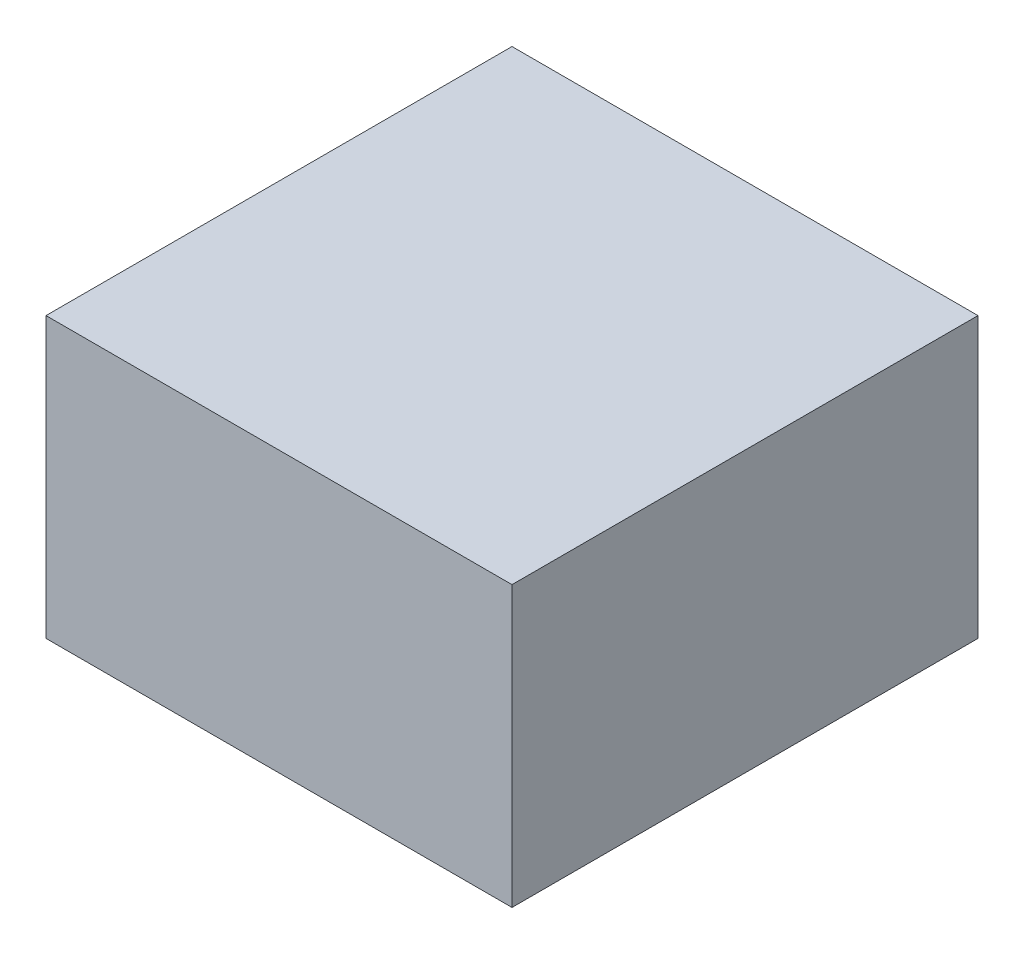
SolidWorks part; units mm, degrees
ref_plane "Front Plane" through (0, 0, 0) normal (0, 0, 1) x (1, 0, 0)
ref_plane "Top Plane" through (0, 0, 0) normal (0, 1, 0) x (1, 0, 0)
ref_plane "Right Plane" through (0, 0, 0) normal (1, 0, 0) x (0, 0, -1)
sketch "Sketch1" plane through (0, 0, 0) normal (0, 1, 0) x (1, 0, 0)
  line L0 (0, 0) -> (0, 31.75)
  line L1 (0, 31.75) -> (31.75, 31.75)
  line L2 (31.75, 31.75) -> (31.75, 0)
  line L3 (31.75, 0) -> (0, 0)
  dimension "D1" = 31.75
  dimension "D2" = 31.75
extrude "Boss-Extrude1" add sketch "Sketch1" along normal blind 19.05
